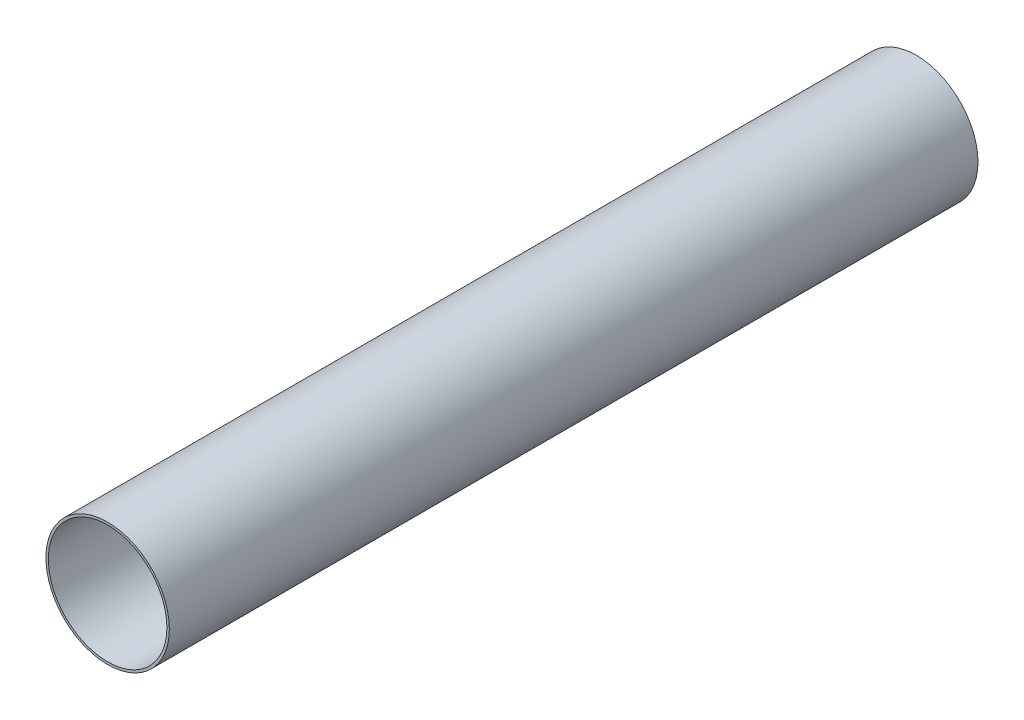
SolidWorks part; units mm, degrees
ref_plane "Front Plane" through (0, 0, 0) normal (0, 0, 1) x (1, 0, 0)
ref_plane "Top Plane" through (0, 0, 0) normal (0, 1, 0) x (1, 0, 0)
ref_plane "Right Plane" through (0, 0, 0) normal (1, 0, 0) x (0, 0, -1)
sketch "Sketch1" plane through (0, 0, 0) normal (0, 0, 1) x (1, 0, 0)
  circle A0 centre (0, 0) radius 11.45
  circle A1 centre (0, 0) radius 11
  dimension "D1" = 22.9
  dimension "D2" = 22
extrude "Boss-Extrude1" add sketch "Sketch1" along normal blind 150
